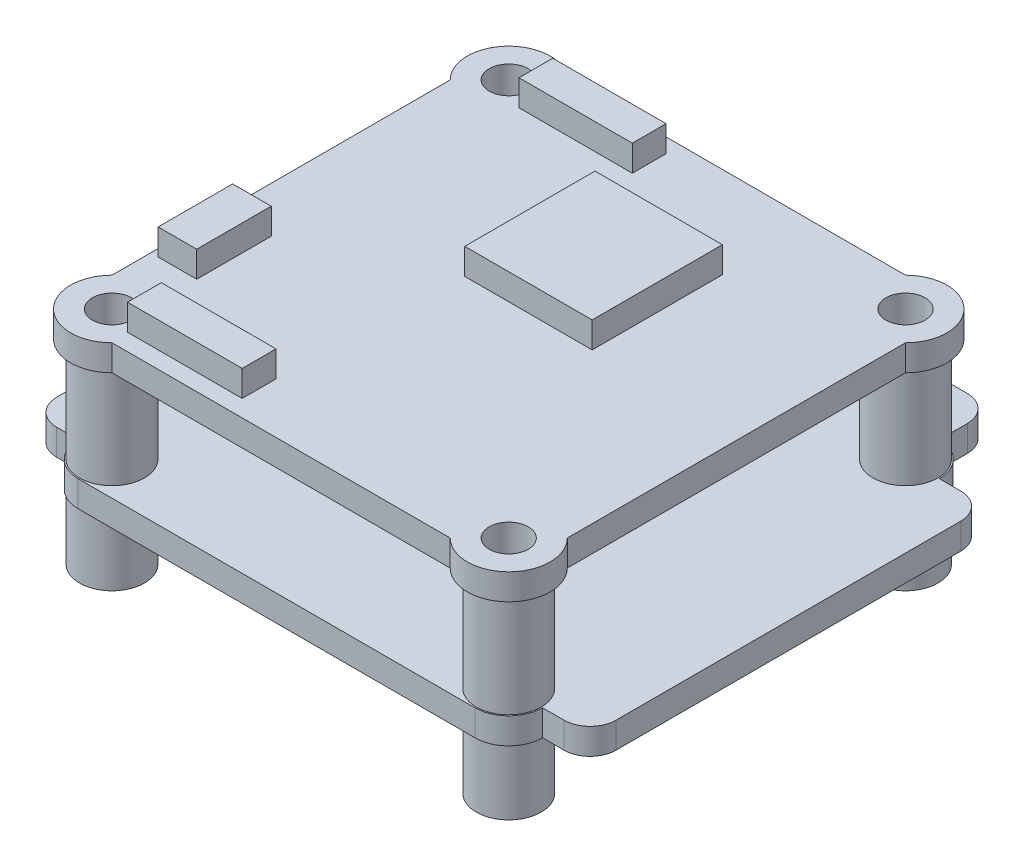
SolidWorks part; units mm, degrees
ref_plane "前视基准面" through (0, 0, 0) normal (0, 0, 1) x (1, 0, 0)
ref_plane "上视基准面" through (0, 0, 0) normal (0, 1, 0) x (1, 0, 0)
ref_plane "右视基准面" through (0, 0, 0) normal (1, 0, 0) x (0, 0, -1)
sketch "草图1" plane through (0, 0, 0) normal (0, 1, 0) x (1, 0, 0)
  line L0 (-21.5, -22) -> (-19.5, -22)
  line L1 (-21.5, 22) -> (21.5, 22)
  line L2 (-21.5, 22) -> (-21.5, -22)
  line L3 (-19.5, -23) -> (19.5, -23)
  line L4 (21.5, 22) -> (21.5, -22)
  line L5 (-21.5, 22) -> (21.5, -22) construction
  line L6 (-21.5, -22) -> (21.5, 22) construction
  line L7 (-15.25, 15.25) -> (15.25, 15.25) construction
  line L8 (-15.25, 15.25) -> (-15.25, -15.25) construction
  line L9 (-15.25, -15.25) -> (15.25, -15.25) construction
  line L10 (15.25, 15.25) -> (15.25, -15.25) construction
  line L11 (-15.25, 15.25) -> (15.25, -15.25) construction
  line L12 (-15.25, -15.25) -> (15.25, 15.25) construction
  line L13 (-19.5, -23) -> (-19.5, -22)
  line L14 (19.5, -22) -> (19.5, -23)
  line L15 (19.5, -22) -> (21.5, -22)
  point P0 (0, 0)
  point P6 (0, 0)
  dimension "D1" = 43
  dimension "D3" = 30.5
  dimension "D4" = 30.5
  dimension "D5" = 1
  dimension "D6" = 2
  dimension "2" = 2
extrude "凸台-拉伸1" add sketch "草图1" along normal blind 2
sketch "草图2" plane through (0, 0, 0) normal (0, -1, 0) x (1, 0, 0)
  line L1 (-15.25, 15.25) -> (15.25, 15.25) construction
  line L2 (-15.25, 15.25) -> (-15.25, -15.25) construction
  line L3 (-15.25, -15.25) -> (15.25, -15.25) construction
  line L4 (15.25, 15.25) -> (15.25, -15.25) construction
  line L5 (-15.25, 15.25) -> (15.25, -15.25) construction
  line L6 (-15.25, -15.25) -> (15.25, 15.25) construction
  circle A0 centre (-15.25, 15.25) radius 2.5
  circle A1 centre (15.25, 15.25) radius 2.5
  circle A2 centre (15.25, -15.25) radius 2.5
  circle A3 centre (-15.25, -15.25) radius 2.5
  point P0 (0, 0)
  dimension "D3" = 5
  dimension "D1" = 30.5
  dimension "D2" = 30.5
  dimension "D4" = 4
extrude "凸台-拉伸2" add sketch "草图2" along normal blind 5
sketch "草图3" plane through (0, 2, 0) normal (0, 1, 0) x (1, 0, 0)
  line L1 (-15.25, 15.25) -> (15.25, 15.25) construction
  line L2 (-15.25, 15.25) -> (-15.25, -15.25) construction
  line L3 (-15.25, -15.25) -> (15.25, -15.25) construction
  line L4 (15.25, 15.25) -> (15.25, -15.25) construction
  line L5 (-15.25, 15.25) -> (15.25, -15.25) construction
  line L6 (-15.25, -15.25) -> (15.25, 15.25) construction
  circle A0 centre (-15.25, 15.25) radius 2.5
  circle A1 centre (15.25, 15.25) radius 2.5
  circle A2 centre (15.25, -15.25) radius 2.5
  circle A3 centre (-15.25, -15.25) radius 2.5
  point P0 (0, 0)
  dimension "D3" = 5
  dimension "D1" = 30.5
  dimension "D2" = 30.5
  dimension "D4" = 4
extrude "凸台-拉伸3" add sketch "草图3" along normal blind 8
sketch "草图4" plane through (0, 10, 0) normal (0, 1, 0) x (1, 0, 0)
  line L1 (-13, 17.5) -> (13, 17.5)
  line L2 (-17.5, 13) -> (-17.5, -13)
  line L3 (-13, -17.5) -> (13, -17.5)
  line L4 (17.5, 13) -> (17.5, -13)
  line L5 (-13, 13) -> (17.5, -17.5) construction
  line L6 (-17.5, -17.5) -> (17.5, 17.5) construction
  arc A0 (17.5, 13) -> (13, 17.5) centre (15.25, 15.25) ccw
  arc A1 (13, -17.5) -> (17.5, -13) centre (15.25, -15.25) ccw
  arc A2 (-17.5, -13) -> (-13, -17.5) centre (-15.25, -15.25) ccw
  arc A3 (-13, 17.5) -> (-17.5, 13) centre (-15.25, 15.25) ccw
  point P0 (0, 0)
  dimension "D2" = 35
  dimension "D3" = 4
extrude "凸台-拉伸4" add sketch "草图4" along normal blind 2
sketch "草图5" plane through (0, 0, 0) normal (0, -1, 0) x (1, 0, 0)
  line L0 (15.25, 17.85) -> (-15.25, 17.85)
  line L3 (21.5, -15.25) -> (17.85, -15.25)
  line L4 (15.25, -22) -> (15.25, -17.85)
  line L5 (18.375, -18.625) -> (17.0165, -17.1578) construction
  line L6 (21.5, -15.25) -> (15.25, -22) construction
  line L9 (-21.5, -15.25) -> (-17.85, -15.25)
  line L10 (-15.25, -22) -> (-15.25, -17.85)
  line L11 (-18.375, -18.625) -> (-17.0165, -17.1578) construction
  line L12 (-21.5, -15.25) -> (-15.25, -22) construction
  line L15 (21.5, 15.25) -> (17.85, 15.25)
  line L17 (18.375, 18.625) -> (17.0165, 17.1578) construction
  line L18 (21.5, 15.25) -> (18.375, 18.625) construction
  line L21 (-21.5, 15.25) -> (-17.85, 15.25)
  line L23 (-18.375, 18.625) -> (-17.0165, 17.1578) construction
  line L24 (-21.5, 15.25) -> (-15.25, 22) construction
  line L25 (21.5, 15.25) -> (21.5, 22)
  line L26 (-21.5, -15.25) -> (-21.5, -22)
  line L27 (15.25, -22) -> (21.5, -22)
  line L33 (-21.5, 22) -> (-21.5, -22)
  line L34 (-19.5, 22) -> (-21.5, 22)
  line L35 (-19.5, 23) -> (-19.5, 22)
  line L36 (19.5, 23) -> (-19.5, 23)
  line L37 (19.5, 22) -> (19.5, 23)
  line L38 (21.5, 22) -> (19.5, 22)
  line L39 (21.5, -22) -> (21.5, 22)
  line L40 (-21.5, -22) -> (21.5, -22)
  line L41 (-21.5, 22) -> (-21.5, 15.25)
  line L42 (-19.5, 22) -> (-21.5, 22)
  line L43 (-19.5, 23) -> (-19.5, 22)
  line L44 (19.5, 23) -> (-19.5, 23)
  line L45 (19.5, 22) -> (19.5, 23)
  line L46 (21.5, 22) -> (19.5, 22)
  line L47 (21.5, -22) -> (21.5, -15.25)
  line L48 (-21.5, -22) -> (-15.25, -22)
  arc A0 (15.25, -17.85) -> (17.85, -15.25) centre (15.25, -15.25) ccw
  arc A1 (-17.85, -15.25) -> (-15.25, -17.85) centre (-15.25, -15.25) ccw
  arc A2 (-15.25, 17.85) -> (-17.85, 15.25) centre (-15.25, 15.25) ccw
  arc A3 (17.85, 15.25) -> (15.25, 17.85) centre (15.25, 15.25) ccw
  point P4 (18.375, -18.625)
  point P11 (-18.375, -18.625)
  point P18 (18.375, 18.625)
  point P25 (-18.375, 18.625)
  dimension "D1" = 5.2
  dimension "D3" = 0
  dimension "D2" = 4
extrude "切除-拉伸1" cut sketch "草图5" against normal blind 2
fillet "圆角1" radius 2 6 edges at (-21.5, 1, 15.25) (-21.5, 1, -15.25) (-15.25, 1, -22) (15.25, 1, -22) (21.5, 1, -15.25) (21.5, 1, 15.25)
sketch "草图6" plane through (0, 12, 0) normal (0, 1, 0) x (1, 0, 0)
  line L1 (-13, 16.3852) -> (-4.2898, 16.3852)
  line L2 (-13, 16.3852) -> (-13, 13.7877)
  line L3 (-13, 13.7877) -> (-4.2898, 13.7877)
  line L4 (-4.2898, 16.3852) -> (-4.2898, 13.7877)
  line L5 (-13, 16.3852) -> (-4.2898, 13.7877) construction
  line L6 (-13, 13.7877) -> (-4.2898, 16.3852) construction
  line L7 (-16.938, -10.0148) -> (-13.9715, -10.0148)
  line L8 (-16.938, -10.0148) -> (-16.938, -4.2849)
  line L9 (-16.938, -4.2849) -> (-13.9715, -4.2849)
  line L10 (-13.9715, -10.0148) -> (-13.9715, -4.2849)
  line L11 (-16.938, -10.0148) -> (-13.9715, -4.2849) construction
  line L12 (-16.938, -4.2849) -> (-13.9715, -10.0148) construction
  line L13 (-13.1057, -16.2019) -> (-4.2898, -16.2019)
  line L14 (-13.1057, -16.2019) -> (-13.1057, -13.6043)
  line L15 (-13.1057, -13.6043) -> (-4.2898, -13.6043)
  line L16 (-4.2898, -16.2019) -> (-4.2898, -13.6043)
  line L17 (-13.1057, -16.2019) -> (-4.2898, -13.6043) construction
  line L18 (-13.1057, -13.6043) -> (-4.2898, -16.2019) construction
  line L19 (-3.8643, 10.4934) -> (5.9333, 10.4934)
  line L20 (-3.8643, 10.4934) -> (-3.8643, 0.4791)
  line L21 (-3.8643, 0.4791) -> (5.9333, 0.4791)
  line L22 (5.9333, 10.4934) -> (5.9333, 0.4791)
  line L23 (-3.8643, 10.4934) -> (5.9333, 0.4791) construction
  line L24 (-3.8643, 0.4791) -> (5.9333, 10.4934) construction
  point P4 (-8.6449, 15.0865)
  point P9 (-15.4548, -7.1499)
  point P14 (-8.6978, -14.9031)
  point P15 (1.0345, 5.4862)
extrude "凸台-拉伸5" add sketch "草图6" along normal blind 2
sketch "草图7" plane through (0, 12, 0) normal (0, 1, 0) x (1, 0, 0)
  circle A0 centre (-15.25, 15.25) radius 1.5
  circle A1 centre (15.25, 15.25) radius 1.5
  circle A2 centre (15.25, -15.25) radius 1.5
  circle A3 centre (-15.25, -15.25) radius 1.5
  dimension "D1" = 3
  dimension "D2" = 4
extrude "切除-拉伸2" cut sketch "草图7" against normal through all
